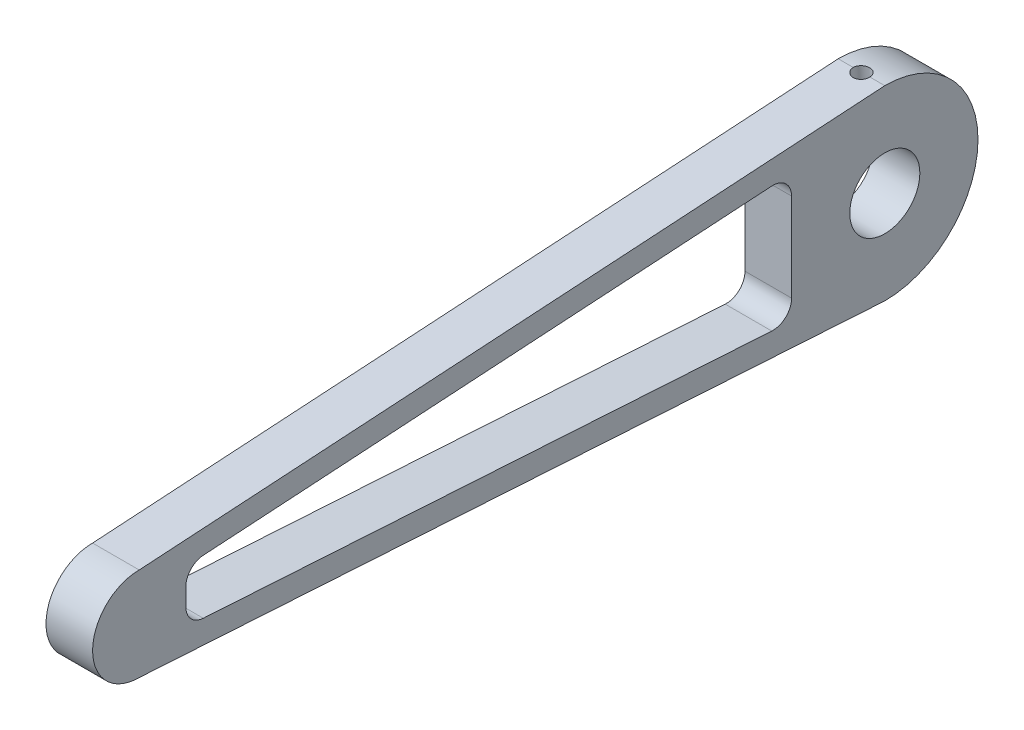
SolidWorks part; units mm, degrees
material "6061-T6 (SS)"
ref_plane "Front Plane" through (0, 0, 0) normal (0, 0, 1) x (1, 0, 0)
ref_plane "Top Plane" through (0, 0, 0) normal (0, 1, 0) x (1, 0, 0)
ref_plane "Right Plane" through (0, 0, 0) normal (1, 0, 0) x (0, 0, -1)
sketch "Sketch1" plane through (0, 0, 0) normal (1, 0, 0) x (0, 0, -1)
  line L0 (0, 12.7) -> (0, -12.7) construction
  line L1 (0, 0) -> (-101.6, 0) construction
  line L2 (0, 12.7) -> (-101.6, 6.35)
  line L3 (0, -12.7) -> (-101.6, -6.35)
  line L4 (-12.7, -6.0213) -> (-12.7, 6.0213)
  line L5 (-95.25, -1.1795) -> (-95.25, 1.1795)
  line L6 (-15.3984, 8.5564) -> (-92.8684, 3.7145)
  line L7 (-92.8684, -3.7145) -> (-15.3984, -8.5564)
  arc A0 (-1.5813, -12.6012) -> (-1.5813, 12.6012) centre (0, 0) ccw
  arc A1 (-101.6, 6.35) -> (-101.6, -6.35) centre (-101.6, 0) ccw
  arc A2 (-12.7, 6.0213) -> (-15.3984, 8.5564) centre (-15.24, 6.0213) ccw
  arc A3 (-12.7, -6.0213) -> (-15.3984, -8.5564) centre (-15.24, -6.0213) cw
  arc A4 (-92.8684, -3.7145) -> (-95.25, -1.1795) centre (-92.71, -1.1795) cw
  arc A5 (-92.8684, 3.7145) -> (-95.25, 1.1795) centre (-92.71, 1.1795) ccw
  circle A6 centre (0, 0) radius 4.7752
  dimension "D1" = 25.4
  dimension "D3" = 12.7
  dimension "D6" = 2.54
  dimension "D7" = 2.54
  dimension "D8" = 2.54
  dimension "D9" = 2.54
  dimension "D10" = 9.5504
  dimension "D2" = 101.6
  dimension "D4" = 3.175
  dimension "D5" = 3.175
extrude "Boss-Extrude1" add sketch "Sketch1" along normal blind 6.35 contours L2 A1 L3 A0 A6 A5 L6 A2 L4 A3 L7 A4 L5
hole_wizard "#4-40 Tapped Hole1" positions "3DSketch1" profile "Sketch2" tap size "#4-40" standard "ANSI Inch"
sketch3d "3DSketch1"
  line L0 (6.35, 12.7, 0) -> (0, 12.7, 0) construction
  point P1 (3.175, 12.7, 0)
  point P4 (1.5875, 12.7, 0)
sketch "Sketch2" plane through (3.175, 12.7, 0) normal (1, 0, 0) x (0, -0.0624, 0.9981)
  line L0 (0, 0) -> (0, 7.9662)
  line L1 (0, 7.9662) -> (1.1303, 7.9662)
  line L2 (1.1303, 7.9662) -> (1.1303, 0)
  line L5 (1.1303, 0) -> (0, 0)
  line L11 (0, -6.35) -> (0, 107.95) construction
  dimension "Thru Tap Drill Dia." = 2.2606
  dimension "Thru Tap Drill Depth" = 7.9662
cosmetic thread "Hole Thread1"
